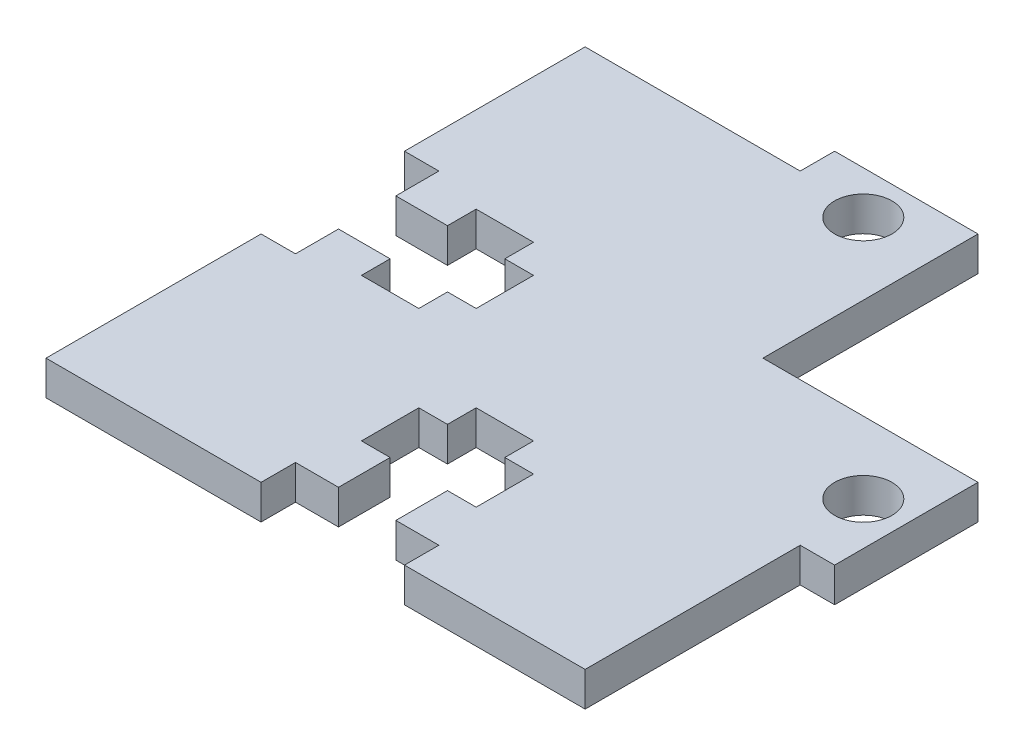
SolidWorks part; units mm, degrees
ref_plane "Front Plane" through (0, 0, 0) normal (0, 0, 1) x (1, 0, 0)
ref_plane "Top Plane" through (0, 0, 0) normal (0, 1, 0) x (1, 0, 0)
ref_plane "Right Plane" through (0, 0, 0) normal (1, 0, 0) x (0, 0, -1)
sketch "Sketch1" plane through (0, 0, 0) normal (0, 1, 0) x (1, 0, 0)
  line L1 (0, 0) -> (50.8, 0)
  line L2 (0, 0) -> (0, 50.8)
  line L3 (0, 50.8) -> (50.8, 50.8)
  line L4 (50.8, 0) -> (50.8, 50.8)
  line L5 (19.05, 50.8) -> (0, 50.8)
  line L6 (19.05, 50.8) -> (19.05, 47.752)
  line L7 (19.05, 47.752) -> (0, 47.752)
  line L8 (0, 50.8) -> (0, 47.752)
  line L9 (31.75, 50.8) -> (50.8, 50.8)
  line L10 (31.75, 50.8) -> (31.75, 47.752)
  line L11 (31.75, 47.752) -> (50.8, 47.752)
  line L12 (50.8, 50.8) -> (50.8, 47.752)
  line L13 (50.8, 50.8) -> (47.752, 50.8)
  line L14 (50.8, 50.8) -> (50.8, 31.75)
  line L15 (50.8, 31.75) -> (47.752, 31.75)
  line L16 (47.752, 50.8) -> (47.752, 31.75)
  line L17 (50.8, 0) -> (47.752, 0)
  line L18 (50.8, 0) -> (50.8, 19.05)
  line L19 (50.8, 19.05) -> (47.752, 19.05)
  line L20 (47.752, 0) -> (47.752, 19.05)
  line L21 (0, 19.05) -> (3.048, 19.05)
  line L22 (19.05, 0) -> (31.75, 0)
  line L23 (19.05, 0) -> (19.05, 3.048)
  line L24 (19.05, 3.048) -> (31.75, 3.048)
  line L25 (31.75, 0) -> (31.75, 3.048)
  line L26 (0, 19.05) -> (0, 31.75)
  line L27 (0, 31.75) -> (3.048, 31.75)
  line L28 (3.048, 19.05) -> (3.048, 31.75)
  point P25 (3.048, 25.4)
  dimension "D1" = 50.8
  dimension "D2" = 50.8
  dimension "D3" = 3.048
  dimension "D4" = 3.048
  dimension "D5" = 3.048
  dimension "D6" = 3.048
  dimension "D7" = 3.048
  dimension "D8" = 3.048
  dimension "D9" = 12.7
  dimension "D10" = 25.4
  dimension "D11" = 12.7
  dimension "D12" = 19.05
  dimension "D13" = 12.7
  dimension "D14" = 19.05
  dimension "D15" = 12.7
  dimension "D16" = 19.05
extrude "Boss-Extrude1" add sketch "Sketch1" along normal blind 3.048 contours L28 L21 L2 L1 L23 L24 L25 L20 L19 L4 L15 L16 L11 L10 L3 L6 L7 L27
sketch "Sketch2" plane through (0, 3.048, 0) normal (0, 1, 0) x (1, 0, 0)
  line L0 (3.048, 19.05) -> (3.048, 31.75) construction
  line L1 (3.048, 27.94) -> (15.24, 27.94)
  line L2 (3.048, 27.94) -> (3.048, 22.86)
  line L3 (3.048, 22.86) -> (15.24, 22.86)
  line L4 (15.24, 27.94) -> (15.24, 22.86)
  line L5 (19.05, 3.048) -> (31.75, 3.048) construction
  line L6 (7.62, 30.48) -> (12.7, 30.48)
  line L7 (7.62, 30.48) -> (7.62, 20.32)
  line L8 (7.62, 20.32) -> (12.7, 20.32)
  line L9 (12.7, 30.48) -> (12.7, 20.32)
  line L10 (22.86, 3.048) -> (27.94, 3.048)
  line L11 (22.86, 3.048) -> (22.86, 15.24)
  line L12 (22.86, 15.24) -> (27.94, 15.24)
  line L13 (27.94, 3.048) -> (27.94, 15.24)
  line L14 (19.05, 50.8) -> (31.75, 50.8) construction
  line L15 (20.32, 12.7) -> (30.48, 12.7)
  line L16 (20.32, 12.7) -> (20.32, 7.62)
  line L17 (20.32, 7.62) -> (30.48, 7.62)
  line L18 (30.48, 12.7) -> (30.48, 7.62)
  line L19 (19.05, 50.8) -> (19.05, 47.752) construction
  line L20 (50.8, 19.05) -> (47.752, 19.05) construction
  line L21 (50.8, 19.05) -> (50.8, 31.75) construction
  line L22 (0, 31.75) -> (0, 47.752) construction
  line L23 (0, 0) -> (19.05, 0) construction
  line L24 (0, 31.75) -> (3.048, 31.75) construction
  line L25 (19.05, 0) -> (19.05, 3.048) construction
  circle A0 centre (25.4, 46.99) radius 2.54
  circle A1 centre (46.99, 25.4) radius 2.54
  point P36 (25.4, 15.24)
  point P39 (3.048, 25.4)
  point P40 (12.7, 25.4)
  point P41 (25.4, 3.048)
  point P44 (25.4, 7.62)
  point P45 (20.32, 10.16)
  line M18 (3.048, 31.75) -> (3.048, 19.05)
  line M23 (19.05, 3.048) -> (31.75, 3.048)
  dimension "D5" = 5.08
  dimension "D6" = 5.08
  dimension "D1" = 3.81
  dimension "D2" = 6.35
  dimension "D3" = 6.35
  dimension "D4" = 3.81
  dimension "D7" = 15.24
  dimension "D8" = 15.24
  dimension "D9" = 5.08
  dimension "D10" = 5.08
  dimension "D11" = 6.35
  dimension "D12" = 6.35
  dimension "D13" = 6.35
  dimension "D14" = 6.35
  dimension "D15" = 10.16
  dimension "D16" = 10.16
  dimension "D17" = 5.08
  dimension "D18" = 5.08
  dimension "D19" = 2.54
  dimension "D20" = 2.54
extrude "Cut-Extrude1" cut sketch "Sketch2" against normal blind 3.048 contours L7 L1 L3 M18 | L9 L1 L7 L3 | L9 L6 L7 L1 | L1 L9 L3 L4 | L9 L3 L7 L8 | L11 L15 L13 L12 | L11 L17 L13 L15 | L18 L15 L13 L17 | L16 L17 L11 L15 | L17 L11 L13 M23 | A1 | A0
sketch "Sketch3" plane through (0, 3.048, 0) normal (0, 1, 0) x (1, 0, 0)
  line L1 (47.752, 31.75) -> (31.75, 31.75)
  line L2 (47.752, 31.75) -> (47.752, 47.752)
  line L3 (47.752, 47.752) -> (31.75, 47.752)
  line L4 (31.75, 31.75) -> (31.75, 47.752)
extrude "Cut-Extrude2" cut sketch "Sketch3" against normal blind 3.048
